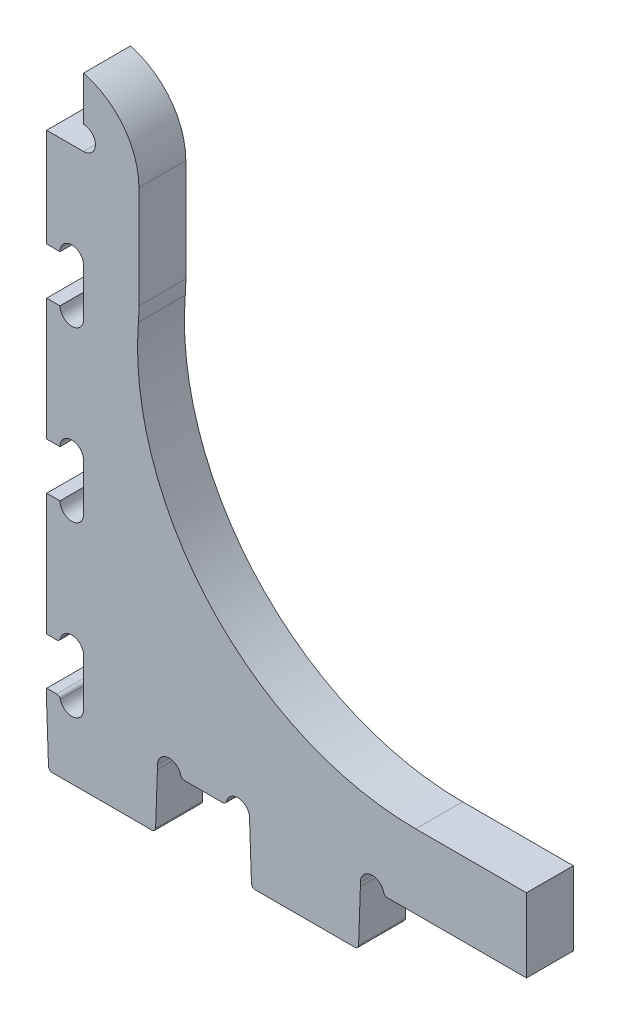
SolidWorks part; units mm, degrees
ref_plane "Front Plane" through (0, 0, 0) normal (0, 0, 1) x (1, 0, 0)
ref_plane "Top Plane" through (0, 0, 0) normal (0, 1, 0) x (1, 0, 0)
ref_plane "Right Plane" through (0, 0, 0) normal (1, 0, 0) x (0, 0, -1)
sketch "Sketch1" plane through (0, 0, 0) normal (0, 0, 1) x (1, 0, 0)
  line L0 (0, 0) -> (0, 153) construction
  line L1 (0, 0) -> (80, 0) construction
  line L2 (80, 0) -> (80, 153) construction
  line L3 (80, 153) -> (0, 153) construction
  line L4 (80, 0) -> (210, 0) construction
  line L5 (210, 0) -> (210, 20) construction
  line L6 (210, 20) -> (105, 153) construction
  line L7 (105, 153) -> (80, 153) construction
  line L8 (105, 153) -> (210, 153) construction
  line L9 (210, 153) -> (210, 20) construction
  line L10 (105, 153) -> (105, 103)
  line L11 (210, 20) -> (180, 20)
  line L12 (80, 153) -> (80, 0)
  line L13 (80, 0) -> (80, -16.05)
  line L14 (210, 0) -> (210, 20)
  line L15 (105, 153) -> (80, 153)
  line L16 (80, -16.05) -> (110, -16.05)
  line L17 (110, -16.05) -> (110, 0)
  line L18 (171.4, 0) -> (210, 0)
  line L19 (135, 0) -> (135, -16.05)
  line L20 (135, -16.05) -> (165, -16.05)
  line L21 (165, -16.05) -> (165, 0)
  line L22 (128.6, 0) -> (116.4, 0)
  arc A0 (105, 103) -> (180, 20) centre (180, 95.3855) ccw
  arc A1 (116.4, 0) -> (110, 0) centre (113.2, 0) ccw
  arc A2 (135, 0) -> (128.6, 0) centre (131.8, 0) ccw
  arc A3 (171.4, 0) -> (165, 0) centre (168.2, 0) ccw
  dimension "D11" = 6.4
  dimension "D1" = 210
  dimension "D2" = 80
  dimension "D3" = 153
  dimension "D4" = 25
  dimension "D5" = 20
  dimension "D6" = 30
  dimension "D7" = 50
  dimension "D8" = 30
  dimension "D9" = 25
  dimension "D10" = 16.05
extrude "Boss-Extrude1" add sketch "Sketch1" along normal blind 12.7
fillet "Fillet1" radius 50 1 edges at (105, 103, 6.35)
fillet "Fillet2" radius 20 1 edges at (105, 153, 6.35)
sketch "Sketch2" plane through (0, 0, 12.7) normal (0, 0, 1) x (1, 0, 0)
  line L0 (116.4, 0) -> (128.6, 0) construction
  line L1 (80, 153) -> (80, -16.05) construction
  line L2 (83.6, 15.7) -> (80, 15.7)
  line L3 (80, 3) -> (90, 3) construction
  line L4 (80, 3) -> (80, 15.7)
  line L5 (80, 15.7) -> (90, 15.7) construction
  line L6 (90, 3) -> (90, 15.7)
  line L7 (80, 3) -> (83.6, 3)
  line L9 (80, 153) -> (80, 3) construction
  arc A0 (90, 15.7) -> (83.6, 15.7) centre (86.8, 15.7) ccw
  arc A1 (83.6, 3) -> (90, 3) centre (86.8, 3) ccw
  dimension "D3" = 6.4
  dimension "D1" = 12.7
  dimension "D2" = 10
  dimension "D4" = 3
extrude "Cut-Extrude1" cut sketch "Sketch2" against normal through all
chamfer "Chamfer1" distance 15 angle 2 4 edges at (80, -16.05, 6.35) (165, -16.05, 6.35) (135, -16.05, 6.35) (110, -16.05, 6.35)
fillet "Fillet3" radius 1 9 edges at (83.6, 3, 6.35) (83.6, 15.7, 6.35) (116.4, 0, 6.35) (128.6, 0, 6.35) (171.4, 0, 6.35) (164.4762, -16.05, 6.35) (135.5238, -16.05, 6.35) (109.4762, -16.05, 6.35) (80.5238, -16.05, 6.35)
pattern_linear "LPattern1" count 3 spacing 45.77 along (0, 1, 0) of "Cut-Extrude1"
sketch "Sketch3" plane through (0, 0, 12.7) normal (0, 0, 1) x (1, 0, 0)
  line L0 (80, 133.95) -> (90, 133.95)
  line L1 (80, 153) -> (80, 107.24) construction
  line L2 (90, 133.95) -> (90, 153) construction
  line L3 (90, 153) -> (80, 153)
  line L4 (80, 153) -> (80, 133.95)
  line L5 (90, 94.54) -> (90, 107.24) construction
  line L6 (90, 153) -> (90, 140.35)
  arc A0 (90, 133.95) -> (90, 140.35) centre (90, 137.15) ccw
  dimension "D2" = 6.4
  dimension "D1" = 19.05
extrude "Cut-Extrude2" cut sketch "Sketch3" against normal through all
